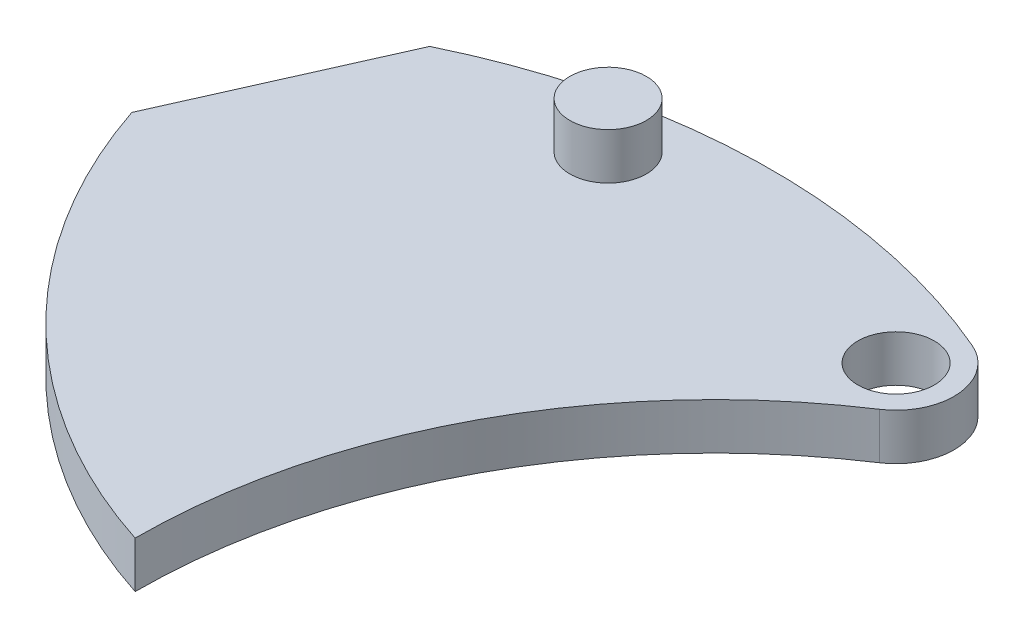
SolidWorks part; units mm, degrees
ref_plane "Front Plane" through (0, 0, 0) normal (0, 0, 1) x (1, 0, 0)
ref_plane "Top Plane" through (0, 0, 0) normal (0, 1, 0) x (1, 0, 0)
ref_plane "Right Plane" through (0, 0, 0) normal (1, 0, 0) x (0, 0, -1)
sketch "Sketch1" plane through (0, 0, 0) normal (0, 1, 0) x (1, 0, 0)
  line L0 (-83.4133, 0) -> (117.6421, 0) construction
  line L1 (0, 90.9683) -> (0, -92.356) construction
  line L2 (0, 0) -> (15.125, 22.967) construction
  line L3 (0, 0) -> (-57.4393, 71.8681) construction
  arc A0 (15.125, 22.967) -> (-17.1691, 21.4819) centre (0, 0) ccw
  arc A1 (15.125, 22.967) -> (0, 0) centre (25, 0) ccw
  arc A2 (-17.1691, 21.4819) -> (0, 0) centre (7.7254, 23.7764) ccw
  arc A3 (50, 0) -> (15.125, 22.967) centre (25, 0) ccw construction
  point P15 (-16.9913, 20.0238)
  dimension "D2" = 25
  dimension "D3" = 25
  dimension "D4" = 72
  dimension "D1" = 27.5
extrude "Boss-Extrude1" add sketch "Sketch1" along normal blind 2
fillet "Fillet1" radius 2.5 2 edges at (15.125, 1, -22.967) (-17.1691, 1, -21.4819)
sketch "Sketch2" plane through (0, 2, 0) normal (0, 1, 0) x (1, 0, 0)
  line L0 (0, 0) -> (9.875, 22.967) construction
  line L1 (0, 0) -> (-4.2269, 24.6401) construction
  circle A0 centre (-4.2269, 24.6401) radius 1.65
  circle A1 centre (9.875, 22.967) radius 1.65
  arc A3 (11.25, 20.8791) -> (10.8625, 25.2637) centre (9.875, 22.967) ccw construction
  circle A4 centre (0, 0) radius 25 construction
  dimension "D1" = 3.3
  dimension "D2" = 3.3
  dimension "D3" = 50
  dimension "D4" = 33
extrude "Cut-Extrude1" cut sketch "Sketch2" against normal blind 2
sketch "Sketch3" plane through (0, 2, 0) normal (0, 1, 0) x (1, 0, 0)
  line L0 (-12.0207, 24.7336) -> (-15.9809, 15.8386)
  arc A0 (10.8625, 25.2637) -> (-15.9644, 22.3917) centre (0, 0) ccw construction
  circle A1 centre (0, 0) radius 22.5 construction
  arc A5 (11.25, 20.8791) -> (0, 0) centre (25, 0) ccw
  arc A6 (11.25, 20.8791) -> (10.8625, 25.2637) centre (9.875, 22.967) ccw
  arc A7 (10.8625, 25.2637) -> (-15.9644, 22.3917) centre (0, 0) ccw
  arc A8 (-15.9644, 22.3917) -> (-16.984, 19.9761) centre (-14.5131, 20.3561) ccw
  arc A9 (-16.984, 19.9761) -> (0, 0) centre (7.7254, 23.7764) ccw
  arc A10 (11.25, 20.8791) -> (0, 0) centre (25, 0) ccw
  arc A11 (11.25, 20.8791) -> (10.8625, 25.2637) centre (9.875, 22.967) ccw
  arc A12 (10.8625, 25.2637) -> (-15.9644, 22.3917) centre (0, 0) ccw
  arc A13 (-15.9644, 22.3917) -> (-16.984, 19.9761) centre (-14.5131, 20.3561) ccw
  arc A14 (-16.984, 19.9761) -> (0, 0) centre (7.7254, 23.7764) ccw
  point P3 (0, 0)
  point P9 (-12.0207, 24.7336)
  arc M10 (10.8625, 25.2637) -> (-15.9644, 22.3917) centre (0, 0) ccw
  arc M11 (-15.9644, 22.3917) -> (-16.984, 19.9761) centre (-14.5131, 20.3561) ccw
  arc M12 (-16.984, 19.9761) -> (0, 0) centre (7.7254, 23.7764) ccw
  dimension "D2" = 45
  dimension "D1" = 0
extrude "Cut-Extrude2" cut sketch "Sketch3" against normal up to next contours L0 M10 M11 M12
sketch "Sketch6" plane through (0, 0, 0) normal (0, -1, 0) x (1, 0, 0)
  circle A0 centre (-4.2269, -24.6401) radius 1.65 construction
  circle A1 centre (-4.2269, -24.6401) radius 1.65
extrude "Boss-Extrude2" add sketch "Sketch6" against normal blind 4 separate body
